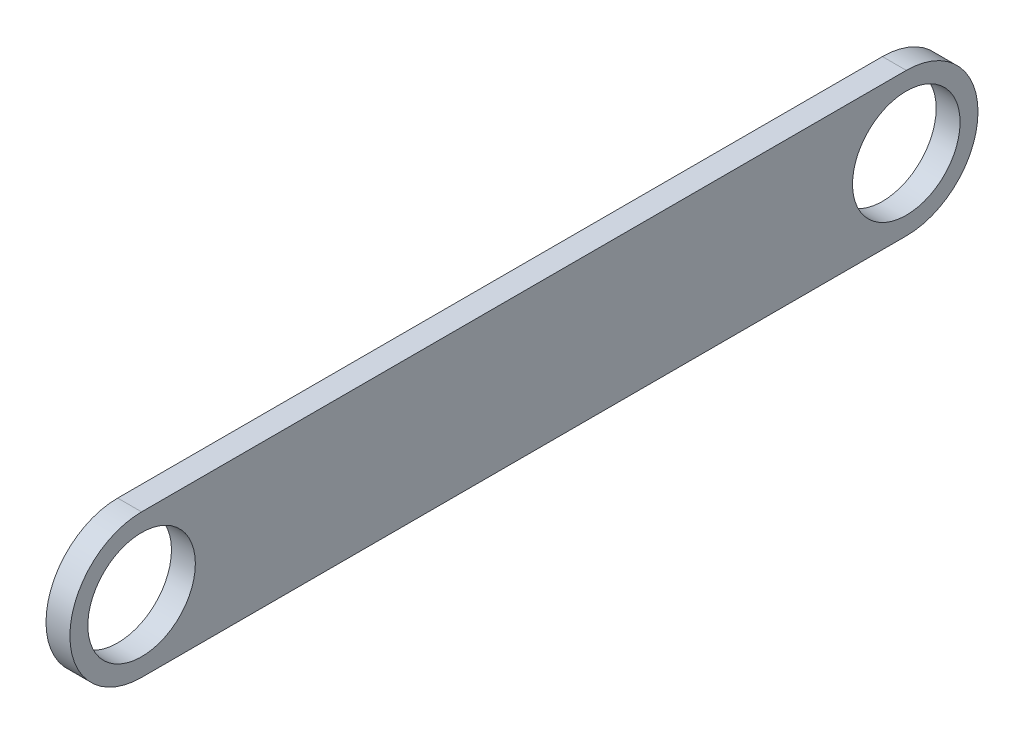
SolidWorks part; units mm, degrees
ref_plane "Front Plane" through (0, 0, 0) normal (0, 0, 1) x (1, 0, 0)
ref_plane "Top Plane" through (0, 0, 0) normal (0, 1, 0) x (1, 0, 0)
ref_plane "Right Plane" through (0, 0, 0) normal (1, 0, 0) x (0, 0, -1)
sketch "Sketch1" plane through (0, 0, 0) normal (1, 0, 0) x (0, 0, -1)
  line L0 (0, 0) -> (203.2, 0) construction
  line L1 (0, -1000) -> (0, 49000) construction
  line L2 (203.2, -1000) -> (203.2, 49000) construction
  line L3 (0, 19.05) -> (203.2, 19.05)
  line L4 (0, -19.05) -> (203.2, -19.05)
  circle A4 centre (0, 0) radius 14.2875
  circle A5 centre (203.2, 0) radius 14.2875
  arc A6 (0, 19.05) -> (0, -19.05) centre (0, 0) ccw
  arc A7 (203.2, -19.05) -> (203.2, 19.05) centre (203.2, 0) ccw
  dimension "D1" = 28.575
  dimension "D4" = 38.1
  dimension "D3" = 28.575
  dimension "D5" = 38.1
  dimension "D2" = 203.2
extrude "Boss-Extrude1" add sketch "Sketch1" along normal blind 6.35
